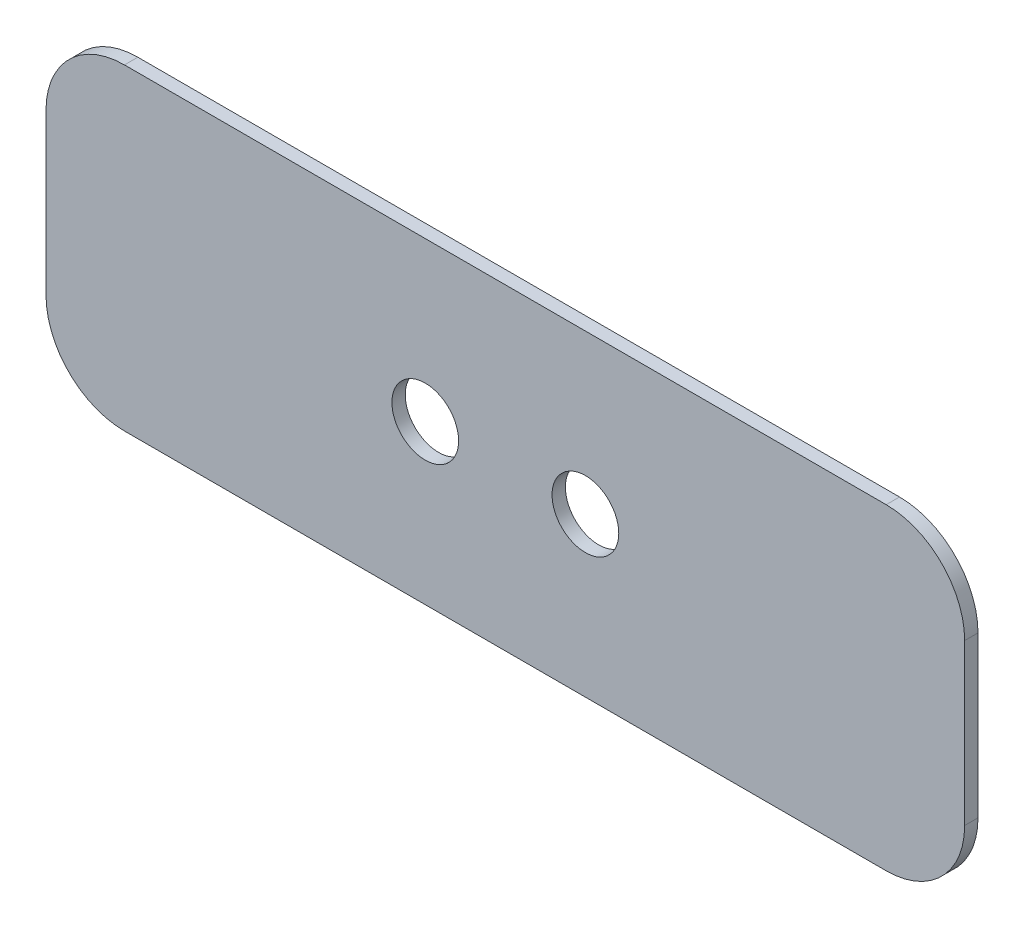
SolidWorks part; units mm, degrees
material "MDF"
ref_plane "Front Plane" through (0, 0, 0) normal (0, 0, 1) x (1, 0, 0)
ref_plane "Top Plane" through (0, 0, 0) normal (0, 1, 0) x (1, 0, 0)
ref_plane "Right Plane" through (0, 0, 0) normal (1, 0, 0) x (0, 0, -1)
sketch "Sketch2" plane through (0, 0, 0) normal (0, 0, 1) x (1, 0, 0)
  line L9 (218.5638, -180.975) -> (218.5638, -104.775)
  line L10 (-181.2258, -218.313) -> (181.2258, -218.313)
  line L11 (-218.5638, -104.775) -> (-218.5638, -180.975)
  line L12 (181.2258, -67.437) -> (-181.2258, -67.437)
  line L13 (218.5638, -180.975) -> (218.5638, -104.775)
  line L14 (-181.2258, -218.313) -> (181.2258, -218.313)
  line L15 (-218.5638, -104.775) -> (-218.5638, -180.975)
  line L16 (181.2258, -67.437) -> (-181.2258, -67.437)
  arc A8 (181.2258, -218.313) -> (218.5638, -180.975) centre (181.2258, -180.975) ccw
  arc A9 (-218.5638, -180.975) -> (-181.2258, -218.313) centre (-181.2258, -180.975) ccw
  arc A10 (-181.2258, -67.437) -> (-218.5638, -104.775) centre (-181.2258, -104.775) ccw
  arc A11 (218.5638, -104.775) -> (181.2258, -67.437) centre (181.2258, -104.775) ccw
  arc A12 (181.2258, -218.313) -> (218.5638, -180.975) centre (181.2258, -180.975) ccw
  arc A13 (-218.5638, -180.975) -> (-181.2258, -218.313) centre (-181.2258, -180.975) ccw
  arc A14 (-181.2258, -67.437) -> (-218.5638, -104.775) centre (-181.2258, -104.775) ccw
  arc A15 (218.5638, -104.775) -> (181.2258, -67.437) centre (181.2258, -104.775) ccw
  dimension "D1" = 0.762
extrude "Boss-Extrude1" add sketch "Sketch2" along normal blind 6.35
sketch "Sketch3" plane through (0, 0, 6.35) normal (0, 0, 1) x (1, 0, 0)
  line L0 (-218.5638, -142.875) -> (218.5638, -142.875) construction
  line L1 (-218.5638, -104.775) -> (-218.5638, -180.975) construction
  line L2 (218.5638, -180.975) -> (218.5638, -104.775) construction
  circle A0 centre (-38.1, -142.875) radius 15.875
  circle A1 centre (38.1, -142.875) radius 15.875
  point P4 (0, -142.875)
  dimension "D1" = 31.75
  dimension "D2" = 38.1
  dimension "D3" = 38.1
extrude "Cut-Extrude1" cut sketch "Sketch3" against normal up to next
equation "\"D3@Sketch3\"=\"D2@Sketch3\""
